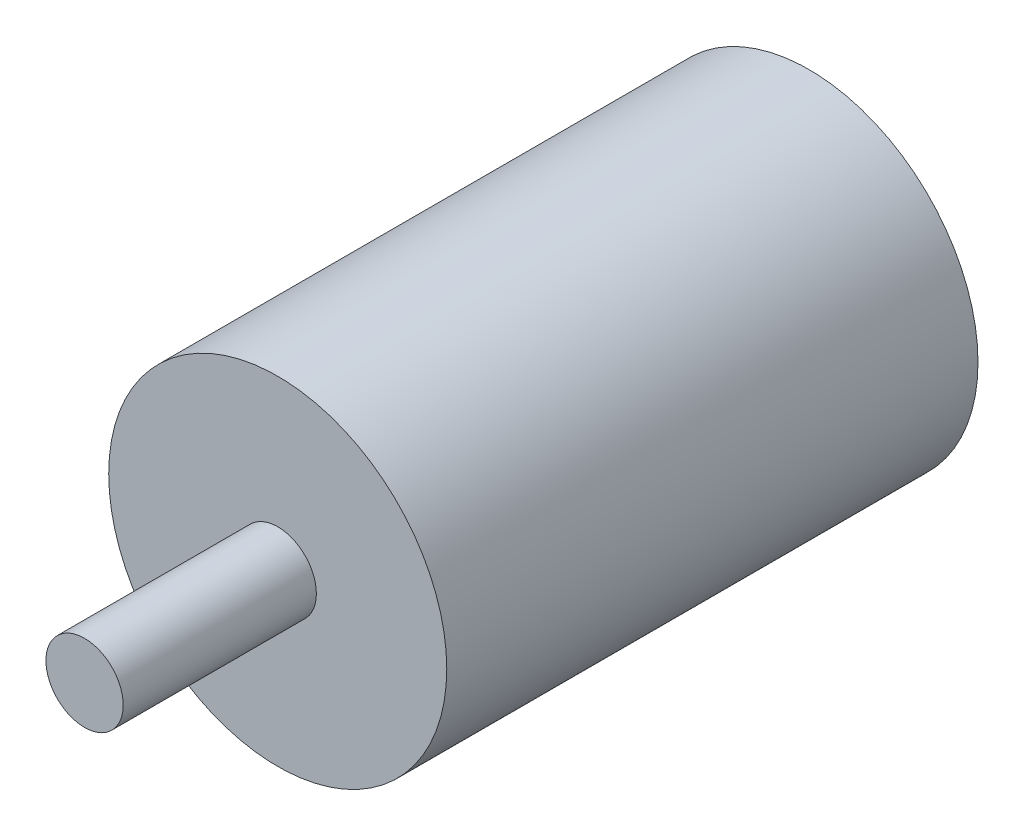
SolidWorks part; units mm, degrees
ref_plane "前视基准面" through (0, 0, 0) normal (0, 0, 1) x (1, 0, 0)
ref_plane "上视基准面" through (0, 0, 0) normal (0, 1, 0) x (1, 0, 0)
ref_plane "右视基准面" through (0, 0, 0) normal (1, 0, 0) x (0, 0, -1)
sketch "草图1" plane through (0, 0, 0) normal (0, 0, 1) x (1, 0, 0)
  circle A0 centre (0, 0) radius 17.5
  dimension "D1" = 35
extrude "凸台-拉伸1" add sketch "草图1" along normal blind 55
sketch "草图2" plane through (0, 0, 55) normal (0, 0, 1) x (1, 0, 0)
  circle A0 centre (0, 0) radius 4
  dimension "D1" = 8
extrude "凸台-拉伸2" add sketch "草图2" along normal blind 20
